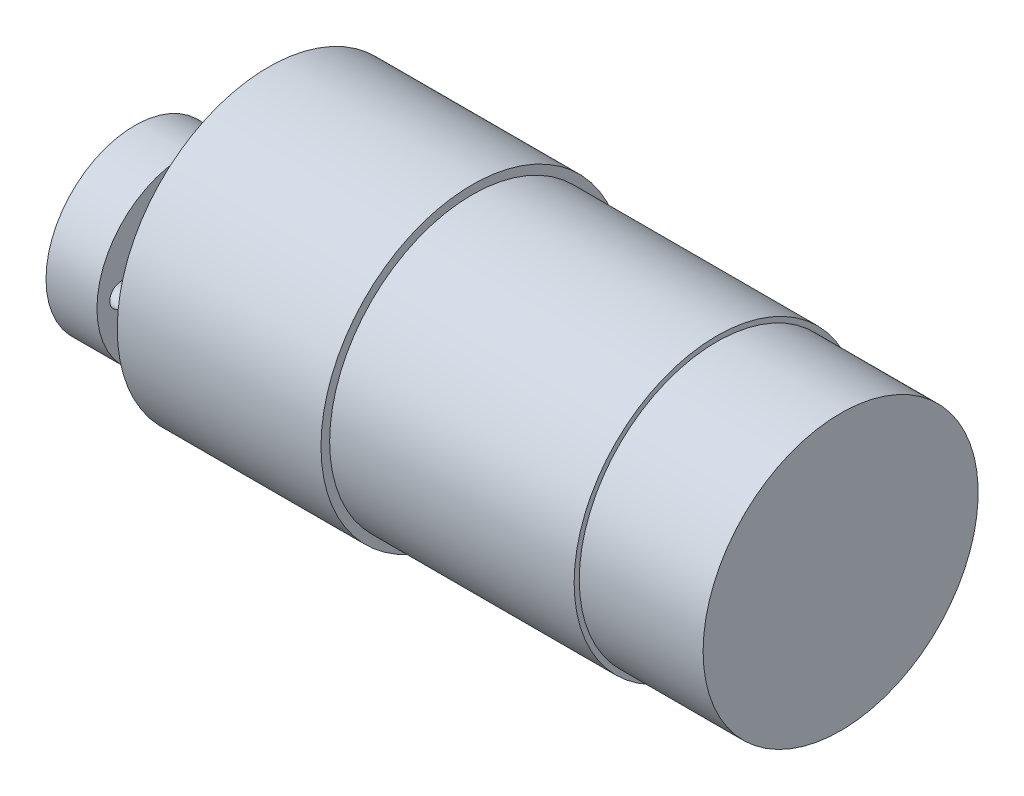
SolidWorks part; units mm, degrees
ref_plane "Face" through (0, 0, 0) normal (0, 0, 1) x (1, 0, 0)
ref_plane "Dessus" through (0, 0, 0) normal (0, 1, 0) x (1, 0, 0)
ref_plane "Droite" through (0, 0, 0) normal (1, 0, 0) x (0, 0, -1)
sketch "Esquisse6" plane through (0, 0, 0) normal (1, 0, 0) x (0, 0, -1)
  circle A0 centre (0, 0) radius 18.8595
  dimension "D1" = 37.719
extrude "Boss.-Extru.2" add sketch "Esquisse6" along normal blind 25.4
sketch "Esquisse7" plane through (25.4, 0, 0) normal (1, 0, 0) x (0, 0, -1)
  circle A0 centre (0, 0) radius 17.78
  dimension "D1" = 35.56
extrude "Boss.-Extru.3" add sketch "Esquisse7" along normal blind 30.48
sketch "Esquisse8" plane through (55.88, 0, 0) normal (1, 0, 0) x (0, 0, -1)
  circle A0 centre (0, 0) radius 17.145
  dimension "D1" = 34.29
extrude "Boss.-Extru.4" add sketch "Esquisse8" along normal blind 15.4432
sketch "Esquisse9" plane through (0, 0, 0) normal (-1, 0, 0) x (0, 0, 1)
  circle A0 centre (0, -6.858) radius 5.969
  dimension "D1" = 11.938
  dimension "D2" = 6.858
extrude "Boss.-Extru.5" add sketch "Esquisse9" along normal blind 6.096
sketch "Esquisse10" plane through (-6.096, 0, 0) normal (-1, 0, 0) x (0, 0, 1)
  circle A0 centre (0, -6.858) radius 4.699
  circle A1 centre (0, -6.858) radius 5.969 construction
  dimension "D1" = 9.398
extrude "Boss.-Extru.6" add sketch "Esquisse10" along normal blind 4.2333
sketch "Esquisse11" plane through (-10.3293, 0, 0) normal (-1, 0, 0) x (0, 0, 1)
  circle A0 centre (0, -6.858) radius 11.0617
  circle A1 centre (0, -6.858) radius 4.699 construction
  dimension "D1" = 22.1234
extrude "Boss.-Extru.7" add sketch "Esquisse11" along normal blind 6.35
sketch "Esquisse12" plane through (-16.6793, 0, 0) normal (-1, 0, 0) x (0, 0, 1)
  circle A0 centre (0, -6.858) radius 4.7752
  circle A1 centre (0, -6.858) radius 11.0617 construction
  dimension "D1" = 9.5504
extrude "Boss.-Extru.8" add sketch "Esquisse12" along normal blind 3.302
hole_wizard "Perçage pour tuyau pour trou taraudé 1/161" positions "Esquisse13" profile "Esquisse15" hole size "1/16" standard "Ansi Inch"
sketch "Esquisse13" plane through (-19.9813, 0, 0) normal (-1, 0, 0) x (0, 0, 1)
  circle A1 centre (0, -6.858) radius 4.7752 construction
  point P0 (0, -6.858)
  point P13 (0, 0)
  point P14 (0, 0)
sketch "Esquisse15" plane through (-19.9813, -6.858, 0) normal (0, 1, 0) x (0, 0, 1)
  line L0 (0, 0) -> (0, 19.9813)
  line L1 (0, 19.9813) -> (3.0734, 19.9813)
  line L2 (3.0734, 19.9813) -> (3.0734, 0)
  line L5 (3.0734, 0) -> (0, 0)
  line L10 (0, 19.9813) -> (-3.0734, 19.9813) construction
  line L11 (0, -6.35) -> (0, 107.95) construction
  dimension "Diamètre du perçage" = 6.1468
  dimension "Profondeur du perçage" = 19.9813
  dimension "Angle de pointe" = 180
sketch "Esquisse16" plane through (0, 0, 0) normal (-1, 0, 0) x (0, 0, 1)
  line L0 (-1.778, -4.4768) -> (1.778, -4.4768)
  arc A0 (-1.778, -4.4768) -> (1.778, -4.4768) centre (0, -6.858) ccw
  point P5 (0, -4.4768)
  dimension "D1" = 5.9436
  dimension "D2" = 3.556
extrude "Boss.-Extru.9" add sketch "Esquisse16" along normal up to surface (19.9813 mm away) up to face at (-19.9813, -6.858, 3.0734)
sketch "Esquisse17" plane through (-19.9813, 0, 0) normal (-1, 0, 0) x (0, 0, 1)
  line L0 (-1.778, -4.4768) -> (1.778, -4.4768)
  arc A3 (-1.778, -4.4768) -> (1.778, -4.4768) centre (0, -6.858) ccw
extrude "Boss.-Extru.10" add sketch "Esquisse17" along normal blind 2.032
sketch "Esquisse18" plane through (-16.6793, 0, 0) normal (-1, 0, 0) x (0, 0, 1)
  circle A1 centre (0, 1.143) radius 1.4605
  circle A2 centre (0, -6.858) radius 4.7752 construction
  circle A3 centre (8.001, -6.858) radius 1.4605
  circle A4 centre (0, -14.859) radius 1.4605
  circle A5 centre (-8.001, -6.858) radius 1.4605
  point P15 (0, -6.858)
  dimension "D2" = 2.921
  dimension "D1" = 8.001
  dimension "D3" = 4
extrude "Enlèv. mat.-Extru.2" cut sketch "Esquisse18" against normal up to next
sketch "Esquisse19" plane through (0, 0, 0) normal (-1, 0, 0) x (0, 0, 1)
  circle A0 centre (9, 13.2288) radius 1.5
  circle A1 centre (0, 0) radius 18.8595 construction
  circle A2 centre (6.9564, -14.4086) radius 1.5
  circle A3 centre (-15.9564, 1.1799) radius 1.5
  point P12 (0, 0)
  dimension "D1" = 3
  dimension "D2" = 16
  dimension "D3" = 9
  dimension "D4" = 3
extrude "Enlèv. mat.-Extru.3" cut sketch "Esquisse19" against normal blind 5
